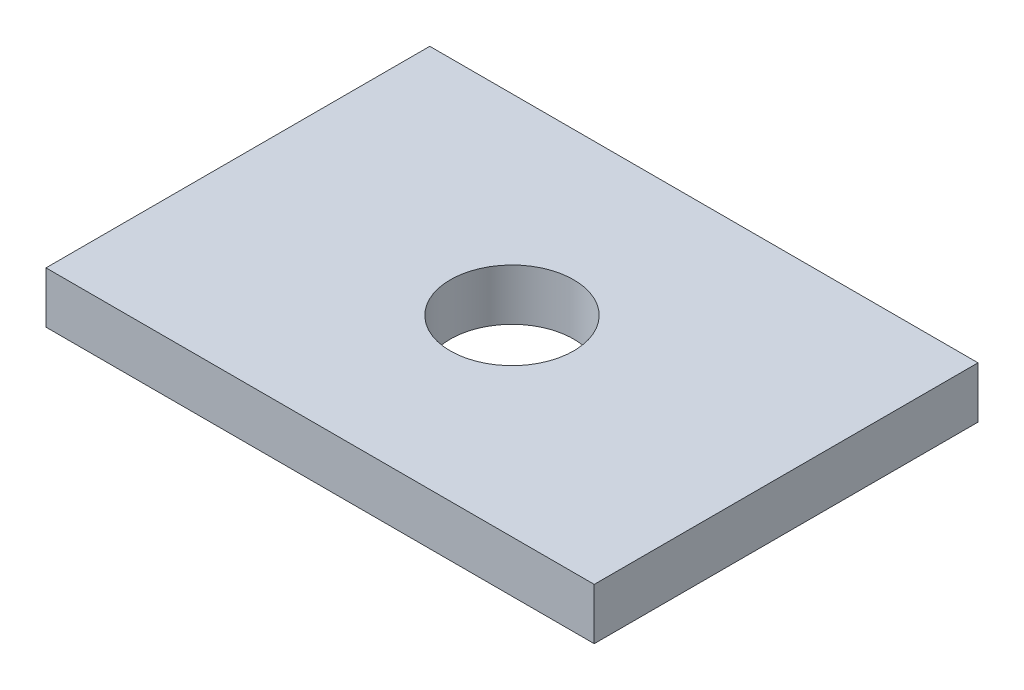
SolidWorks part; units mm, degrees
material "Pine"
ref_plane "Front Plane" through (0, 0, 0) normal (0, 0, 1) x (1, 0, 0)
ref_plane "Top Plane" through (0, 0, 0) normal (0, 1, 0) x (1, 0, 0)
ref_plane "Right Plane" through (0, 0, 0) normal (1, 0, 0) x (0, 0, -1)
sketch "Sketch1" plane through (0, 0, 0) normal (0, 1, 0) x (1, 0, 0)
  line L0 (38.1, 88.9) -> (38.1, 0) construction
  line L1 (0, 0) -> (127, 0)
  line L2 (0, 0) -> (0, 88.9)
  line L3 (0, 88.9) -> (127, 88.9)
  line L4 (127, 0) -> (127, 88.9)
  line L5 (63.5, 88.9) -> (63.5, 0) construction
  line L6 (88.9, 88.9) -> (88.9, 0) construction
  circle A0 centre (63.5, 44.45) radius 14.2875
  dimension "D2" = 28.575
  dimension "D3" = 38.1
  dimension "D5" = 11.1125
  dimension "D1" = 88.9
  dimension "D4" = 127
extrude "Boss-Extrude1" add sketch "Sketch1" along normal blind 11.9062
